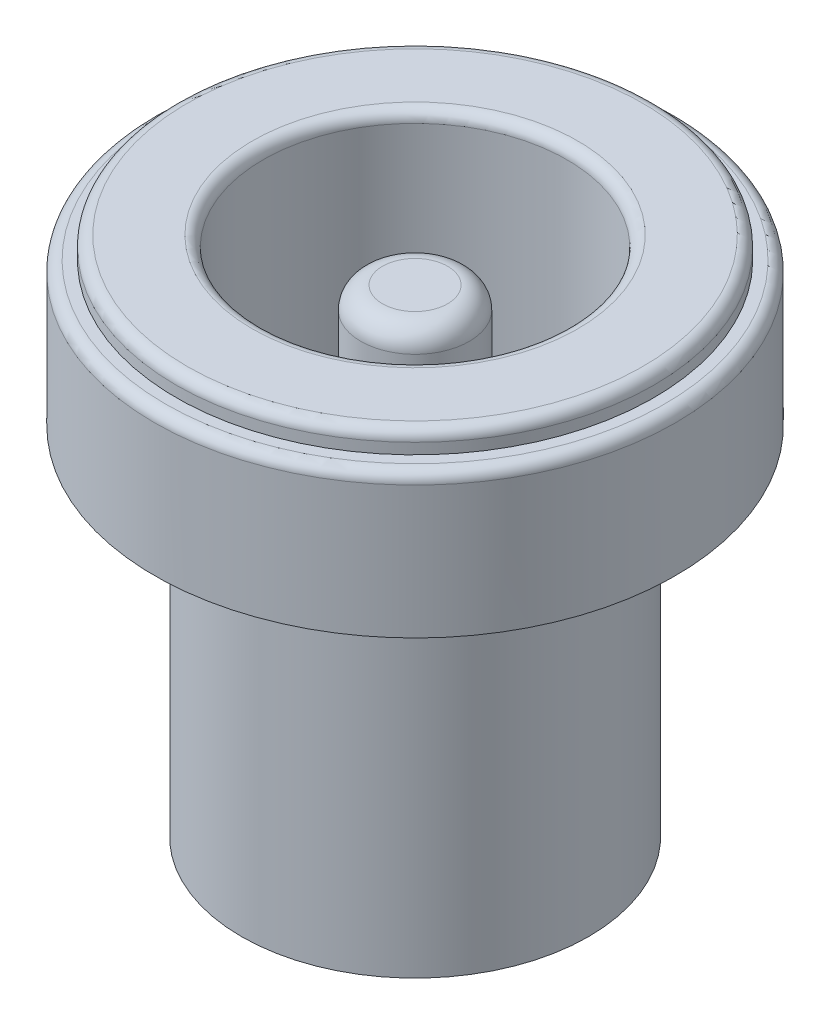
SolidWorks part; units mm, degrees
ref_plane "Front Plane" through (0, 0, 0) normal (0, 0, 1) x (1, 0, 0)
ref_plane "Top Plane" through (0, 0, 0) normal (0, 1, 0) x (1, 0, 0)
ref_plane "Right Plane" through (0, 0, 0) normal (1, 0, 0) x (0, 0, -1)
sketch "Sketch1" plane through (0, 0, 0) normal (0, 0, 1) x (1, 0, 0)
  line L0 (0, 0) -> (5.5, 0)
  line L1 (5.5, 0) -> (5.5, -0.5)
  line L2 (5.5, -0.5) -> (6, -0.5)
  line L3 (6, -0.5) -> (6, -3.8)
  line L4 (6, -3.8) -> (4, -3.8)
  line L5 (4, -3.8) -> (4, -12)
  line L6 (4, -12) -> (0, -12)
  line L7 (0, -12) -> (0, 0)
  point P3 (5.3865, 0)
  dimension "D1" = 12
  dimension "D2" = 3.8
  dimension "D3" = 4
  dimension "D4" = 6
  dimension "D5" = 0.5
revolve "BULK" add sketch "Sketch1" angle 360 about L7
sketch "Sketch2" plane through (0, 0, 0) normal (0, 1, 0) x (1, 0, 0)
  circle A0 centre (0, 0) radius 3.5
  circle A1 centre (0, 0) radius 1.25
  dimension "D1" = 7
  dimension "D2" = 2.5
extrude "INSIDE CUT" cut sketch "Sketch2" against normal blind 10
sketch "Sketch3" plane through (0, 0, 0) normal (0, 1, 0) x (1, 0, 0)
  circle A1 centre (0, 0) radius 1.25
  circle A2 centre (0, 0) radius 1.25
  dimension "D1" = 0
extrude "PIN SHORTENING" cut sketch "Sketch3" against normal blind 1
fillet "Fillet1" radius 0.5 1 edges at (0, -1, 1.25)
fillet "Fillet2" radius 0.25 4 edges at (0, 0, -5.5) (0, -0.5, -6) (0, 0, 3.5) (0, -10, 3.5)
